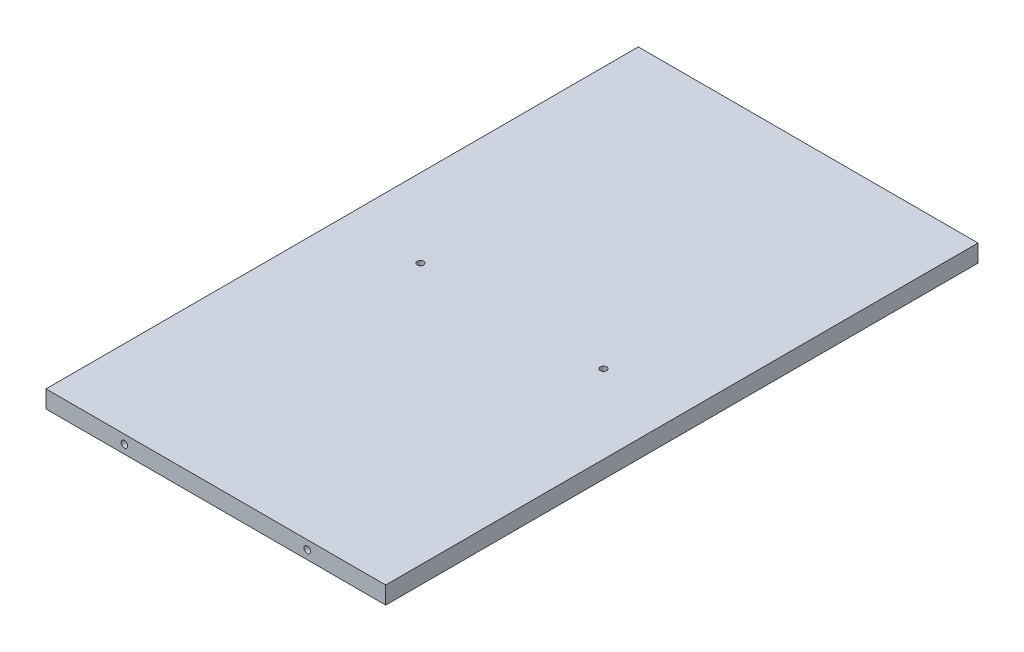
SolidWorks part; units mm, degrees
material "Pin"
ref_plane "Plan de face" through (0, 0, 0) normal (0, 0, 1) x (1, 0, 0)
ref_plane "Plan de dessus" through (0, 0, 0) normal (0, 1, 0) x (1, 0, 0)
ref_plane "Plan de droite" through (0, 0, 0) normal (1, 0, 0) x (0, 0, -1)
sketch "Esquisse1" plane through (0, 0, 0) normal (0, 0, 1) x (1, 0, 0)
  line L1 (-195, -10) -> (195, -10)
  line L2 (-195, -10) -> (-195, 10)
  line L3 (-195, 10) -> (195, 10)
  line L4 (195, -10) -> (195, 10)
  line L5 (-195, -10) -> (195, 10) construction
  line L6 (-195, 10) -> (195, -10) construction
  point P0 (0, 0)
  dimension "D1" = 390
  dimension "D2" = 20
extrude "Boss.-Extru.1" add sketch "Esquisse1" along normal blind 680
sketch "Esquisse2" plane through (0, 0, 680) normal (0, 0, 1) x (1, 0, 0)
  line L0 (-195, 0) -> (-105, 0) construction
  line L1 (-195, 10) -> (-195, -10) construction
  line L2 (195, 0) -> (105, 0) construction
  line L3 (195, -10) -> (195, 10) construction
  circle A0 centre (-105, 0) radius 3.75
  circle A1 centre (105, 0) radius 3.75
  dimension "D3" = 90
  dimension "D1" = 7.5
  dimension "D2" = 7.5
  dimension "D4" = 90
extrude "Enlèv. mat.-Extru.1" cut sketch "Esquisse2" against normal blind 20 and the other way blind 11
sketch "Esquisse4" plane through (0, 0, 0) normal (0, 0, -1) x (-1, 0, 0)
  line L0 (-195, 0) -> (-105, 0) construction
  line L1 (-195, -10) -> (-195, 10) construction
  line L2 (195, 0) -> (105, 0) construction
  line L3 (195, 10) -> (195, -10) construction
  circle A0 centre (-105, 0) radius 3.75
  circle A1 centre (105, 0) radius 3.75
  dimension "D3" = 90
  dimension "D1" = 7.5
  dimension "D2" = 7.5
  dimension "D4" = 90
extrude "Enlèv. mat.-Extru.2" cut sketch "Esquisse4" against normal blind 20
sketch "Esquisse5" plane through (0, 10, 0) normal (0, 1, 0) x (1, 0, 0)
  line L0 (-195, -340) -> (195, -340) construction
  line L1 (-195, -680) -> (-195, 0) construction
  line L2 (195, -680) -> (195, 0) construction
  line L3 (0, 0) -> (0, -680) construction
  line L4 (195, -680) -> (-195, -680) construction
  line L6 (-195, -350) -> (195, -350)
  line L7 (-195, -350) -> (-195, -330)
  line L8 (-195, -330) -> (195, -330)
  line L9 (195, -350) -> (195, -330)
  line L10 (-195, -350) -> (195, -330) construction
  line L11 (-195, -330) -> (195, -350) construction
  circle A0 centre (-105, -340) radius 3.75
  circle A1 centre (105, -340) radius 3.75
  point P11 (0, -340)
  dimension "D5" = 7.5
  dimension "D4" = 7.5
  dimension "D1" = 20
  dimension "D2" = 90
  dimension "D3" = 90
extrude "Enlèv. mat.-Extru.3" cut sketch "Esquisse5" against normal blind 35 contours A1 | A0
equation "\"diamètrebaton\"= 7.5"
equation "\"D5@Esquisse5\"=\"diamètrebaton\""
equation "\"D4@Esquisse5\"=\"diamètrebaton\""
equation "\"D1@Esquisse2\"=\"diamètrebaton\""
equation "\"D2@Esquisse2\"=\"diamètrebaton\""
equation "\"D1@Esquisse4\"=\"diamètrebaton\""
equation "\"D2@Esquisse4\"=\"diamètrebaton\""
